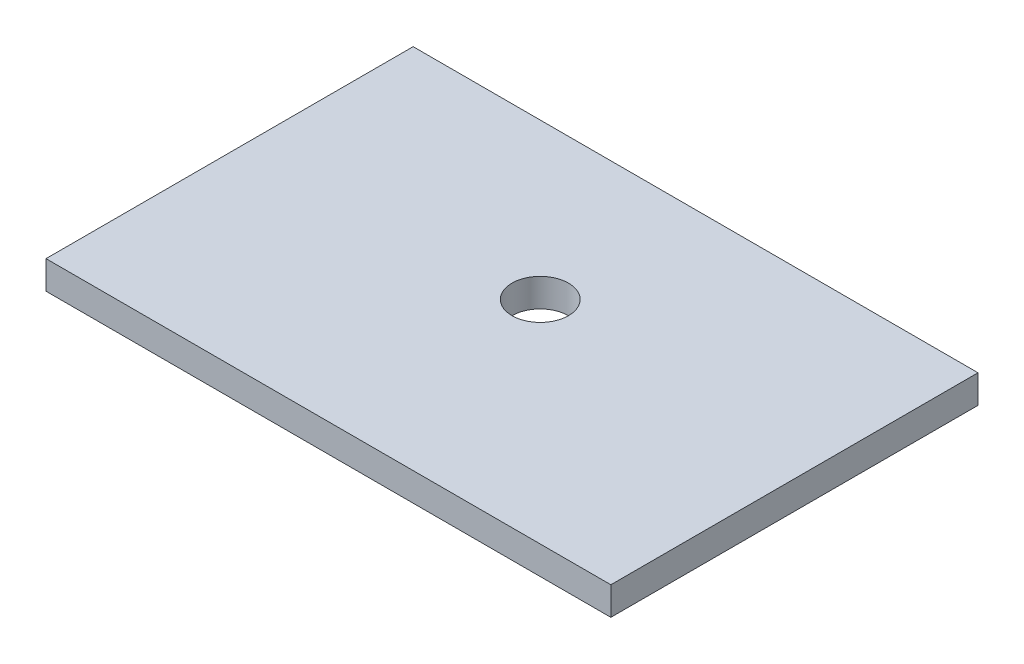
SolidWorks part; units mm, degrees
material "Brass"
ref_plane "Front Plane" through (0, 0, 0) normal (0, 0, 1) x (1, 0, 0)
ref_plane "Top Plane" through (0, 0, 0) normal (0, 1, 0) x (1, 0, 0)
ref_plane "Right Plane" through (0, 0, 0) normal (1, 0, 0) x (0, 0, -1)
sketch "Sketch1" plane through (0, 0, 0) normal (0, 1, 0) x (1, 0, 0)
  line L0 (100, 0) -> (100, -130) construction
  line L1 (0, 0) -> (200, 0)
  line L2 (0, 0) -> (0, -130)
  line L3 (0, -130) -> (200, -130)
  line L4 (200, 0) -> (200, -130)
  circle A0 centre (100, -55) radius 10
  dimension "D3" = 20
  dimension "D1" = 200
  dimension "D2" = 130
  dimension "D4" = 55
extrude "Boss-Extrude1" add sketch "Sketch1" along normal blind 10
